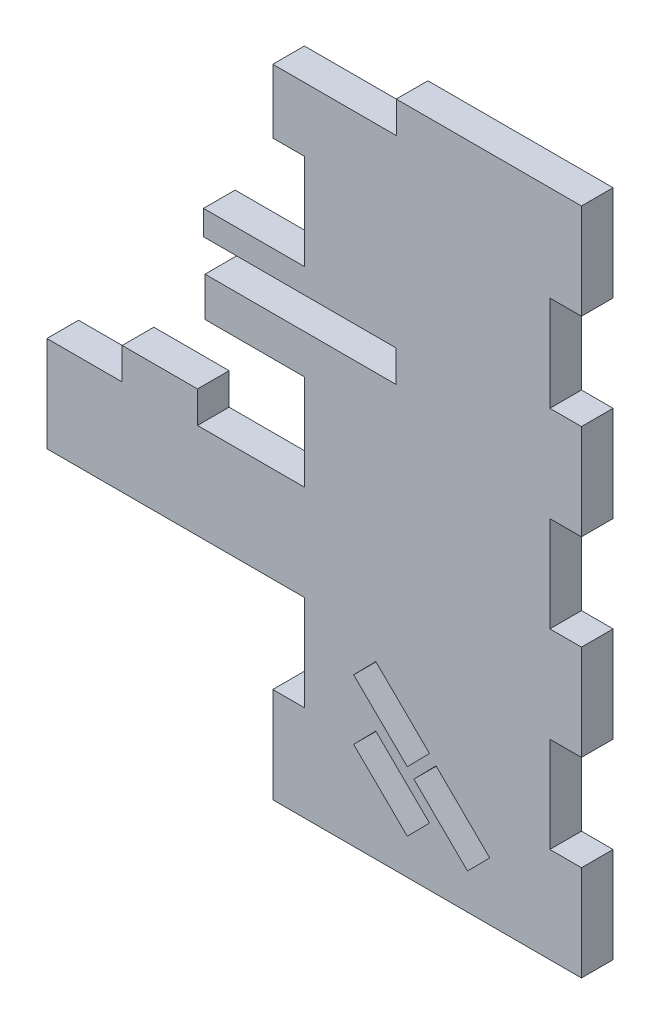
SolidWorks part; units mm, degrees
ref_plane "Front Plane" through (0, 0, 0) normal (0, 0, 1) x (1, 0, 0)
ref_plane "Top Plane" through (0, 0, 0) normal (0, 1, 0) x (1, 0, 0)
ref_plane "Right Plane" through (0, 0, 0) normal (1, 0, 0) x (0, 0, -1)
sketch "Sketch1" plane through (0, 0, 0) normal (0, 0, 1) x (1, 0, 0)
  line L1 (-39.922, 42.4532) -> (12.148, 42.4532)
  line L2 (-39.922, 42.4532) -> (-39.922, -70.3228)
  line L3 (-39.922, -70.3228) -> (12.148, -70.3228)
  line L4 (12.148, 42.4532) -> (12.148, -70.3228)
  dimension "D1" = 112.776
  dimension "D2" = 52.07
extrude "Boss-Extrude1" add sketch "Sketch1" along normal blind 5.334
sketch "Sketch2" plane through (0, 0, 5.334) normal (0, 0, 1) x (1, 0, 0)
  line L0 (-39.922, 42.4532) -> (-39.922, -70.3228) construction
  line L1 (-39.922, 26.3424) -> (-34.588, 26.3424)
  line L2 (-39.922, 26.3424) -> (-39.922, 10.2315)
  line L3 (-39.922, 10.2315) -> (-34.588, 10.2315)
  line L4 (-34.588, 26.3424) -> (-34.588, 10.2315)
  line L5 (-34.588, 26.3424) -> (-34.588, 42.4532) construction
  line L6 (-39.922, -5.8794) -> (-34.588, -5.8794)
  line L7 (-39.922, -5.8794) -> (-39.922, -21.9902)
  line L8 (-39.922, -21.9902) -> (-34.588, -21.9902)
  line L9 (-34.588, -5.8794) -> (-34.588, -21.9902)
  line L10 (-39.922, -38.1011) -> (-34.588, -38.1011)
  line L11 (-39.922, -38.1011) -> (-39.922, -54.2119)
  line L12 (-39.922, -54.2119) -> (-34.588, -54.2119)
  line L13 (-34.588, -38.1011) -> (-34.588, -54.2119)
  line L14 (12.148, 42.4532) -> (-39.922, 42.4532) construction
  line L15 (-34.588, 10.2315) -> (-34.588, -5.8794) construction
  line L16 (-34.588, -21.9902) -> (-34.588, -38.1011) construction
  line L17 (-34.588, -54.2119) -> (-34.588, -70.3228) construction
  line L18 (-39.922, -70.3228) -> (12.148, -70.3228) construction
  line L19 (-13.887, 42.4532) -> (-13.887, -70.3228) construction
  line L20 (6.814, -54.2119) -> (6.814, -70.3228) construction
  line L21 (6.814, -21.9902) -> (6.814, -38.1011) construction
  line L22 (6.814, 10.2315) -> (6.814, -5.8794) construction
  line L23 (6.814, 26.3424) -> (6.814, 42.4532) construction
  line L24 (6.814, -38.1011) -> (6.814, -54.2119)
  line L25 (12.148, -54.2119) -> (6.814, -54.2119)
  line L26 (12.148, -38.1011) -> (12.148, -54.2119)
  line L27 (12.148, -38.1011) -> (6.814, -38.1011)
  line L28 (6.814, -5.8794) -> (6.814, -21.9902)
  line L29 (12.148, -21.9902) -> (6.814, -21.9902)
  line L30 (12.148, -5.8794) -> (12.148, -21.9902)
  line L31 (12.148, -5.8794) -> (6.814, -5.8794)
  line L32 (6.814, 26.3424) -> (6.814, 10.2315)
  line L33 (12.148, 10.2315) -> (6.814, 10.2315)
  line L34 (12.148, 26.3424) -> (12.148, 10.2315)
  line L35 (12.148, 26.3424) -> (6.814, 26.3424)
  line L36 (-34.588, -54.2119) -> (-34.588, -70.3228) construction
  dimension "D1" = 5.334
extrude "Cut-Extrude1" cut sketch "Sketch2" against normal through all
sketch "Sketch3" plane through (0, 0, 5.334) normal (0, 0, 1) x (1, 0, 0)
  line L0 (6.814, -54.2119) -> (6.814, -70.3228) construction
  line L1 (-39.922, -70.3228) -> (12.148, -70.3228) construction
  line L2 (6.814, -70.3228) -> (-39.922, -24.3488) construction
  line L3 (-39.922, -21.9902) -> (-39.922, -38.1011) construction
  line L4 (-22.5448, -41.4427) -> (-13.491, -50.3488)
  line L5 (-22.5448, -41.4427) -> (-26.2854, -45.2453)
  line L6 (-13.491, -50.3488) -> (-17.2316, -54.1514)
  line L7 (-26.2854, -45.2453) -> (-17.2316, -54.1514)
  line L8 (-22.5448, -51.6027) -> (-13.491, -60.5088)
  line L9 (-22.5448, -51.6027) -> (-26.2854, -55.4053)
  line L10 (-13.491, -60.5088) -> (-17.2316, -64.3114)
  line L11 (-26.2854, -55.4053) -> (-17.2316, -64.3114)
  line L12 (-12.3848, -51.6027) -> (-3.331, -60.5088)
  line L13 (-12.3848, -51.6027) -> (-16.1254, -55.4053)
  line L14 (-16.1254, -55.4053) -> (-7.0716, -64.3114)
  line L15 (-3.331, -60.5088) -> (-7.0716, -64.3114)
  dimension "D1" = 5.334
  dimension "D2" = 12.7
  dimension "D3" = 2
extrude "Cut-Extrude2" cut sketch "Sketch3" against normal through all
sketch "Sketch5" plane through (-39.922, 0, 0) normal (-1, 0, 0) x (0, 0, 1)
  line L1 (0, -21.9902) -> (5.334, -21.9902)
  line L2 (0, -21.9902) -> (0, -38.1011)
  line L3 (0, -38.1011) -> (5.334, -38.1011)
  line L4 (5.334, -21.9902) -> (5.334, -38.1011)
extrude "Boss-Extrude2" add sketch "Sketch5" along normal blind 38.1
sketch "Sketch6" plane through (0, -21.9902, 0) normal (0, 1, 0) x (1, 0, 0)
  line L0 (-78.022, 0) -> (-34.588, 0) construction
  line L1 (-65.322, 0) -> (-52.622, 0)
  line L2 (-65.322, 0) -> (-65.322, -5.334)
  line L3 (-65.322, -5.334) -> (-52.622, -5.334)
  line L4 (-52.622, 0) -> (-52.622, -5.334)
  line L6 (-52.622, -3.6121) -> (-39.922, -3.6121) construction
  line L7 (-39.922, -3.6121) -> (-34.588, -3.6121) construction
  line L8 (-34.588, 0) -> (-34.588, -5.334) construction
  line L9 (-65.322, -3.6121) -> (-78.022, -3.6121) construction
  line L10 (-78.022, -5.334) -> (-78.022, 0) construction
  point P17 (-81.9745, -2.0817)
  dimension "D1" = 5.334
extrude "Boss-Extrude3" add sketch "Sketch6" along normal blind 5.334
sketch "Sketch7" plane through (0, 0, 5.334) normal (0, 0, 1) x (1, 0, 0)
  line L0 (-39.922, 10.2315) -> (-39.922, -5.8794) construction
  line L1 (-39.922, 0.7428) -> (-19.1171, 0.7428)
  line L2 (-39.922, 0.7428) -> (-39.922, 6.0768)
  line L3 (-39.922, 6.0768) -> (-19.1171, 6.0768)
  line L4 (-19.1171, 0.7428) -> (-19.1171, 6.0768)
  dimension "D1" = 5.334
extrude "Cut-Extrude4" cut sketch "Sketch7" against normal through all
sketch "Sketch8" plane through (-39.922, 0, 0) normal (-1, 0, 0) x (0, 0, 1)
  line L1 (0, -5.8794) -> (5.334, -5.8794)
  line L2 (0, -5.8794) -> (0, 0.7428)
  line L3 (0, 0.7428) -> (5.334, 0.7428)
  line L4 (5.334, -5.8794) -> (5.334, 0.7428)
extrude "Boss-Extrude4" add sketch "Sketch8" along normal blind 11.43
sketch "Sketch9" plane through (0, 0, 5.334) normal (0, 0, 1) x (1, 0, 0)
  line L1 (-39.922, 42.4532) -> (-19.094, 42.4532)
  line L2 (-39.922, 42.4532) -> (-39.922, 37.1192)
  line L3 (-39.922, 37.1192) -> (-19.094, 37.1192)
  line L4 (-19.094, 42.4532) -> (-19.094, 37.1192)
  dimension "D1" = 5.334
  dimension "D2" = 20.828
extrude "Cut-Extrude5" cut sketch "Sketch9" against normal through all
sketch "Sketch10" plane through (-39.922, 0, 0) normal (-1, 0, 0) x (0, 0, 1)
  line L1 (0, 6.0768) -> (5.334, 6.0768)
  line L2 (0, 6.0768) -> (0, 10.2315)
  line L3 (0, 10.2315) -> (5.334, 10.2315)
  line L4 (5.334, 6.0768) -> (5.334, 10.2315)
extrude "Boss-Extrude5" add sketch "Sketch10" along normal blind 11.684
equation "\"MDF\"= .21in"
equation "\"Foamcore\"= .13in"
equation "\"Gmaterial\"= \"MDF\""
equation "\"D2@Sketch1\"=\"MDF\"+1.63+\"MDF\""
equation "\"D1@Boss-Extrude1\"=\"MDF\""
equation "\"D1@Sketch3\"=\"MDF\""
equation "\"D2@Sketch3\"=.5"
equation "\"D1@Sketch6\"=\"MDF\""
equation "\"D1@Sketch7\"=\"MDF\""
equation "\"D1@Sketch9\"=\"MDF\""
equation "\"D2@Sketch9\"=.82"
